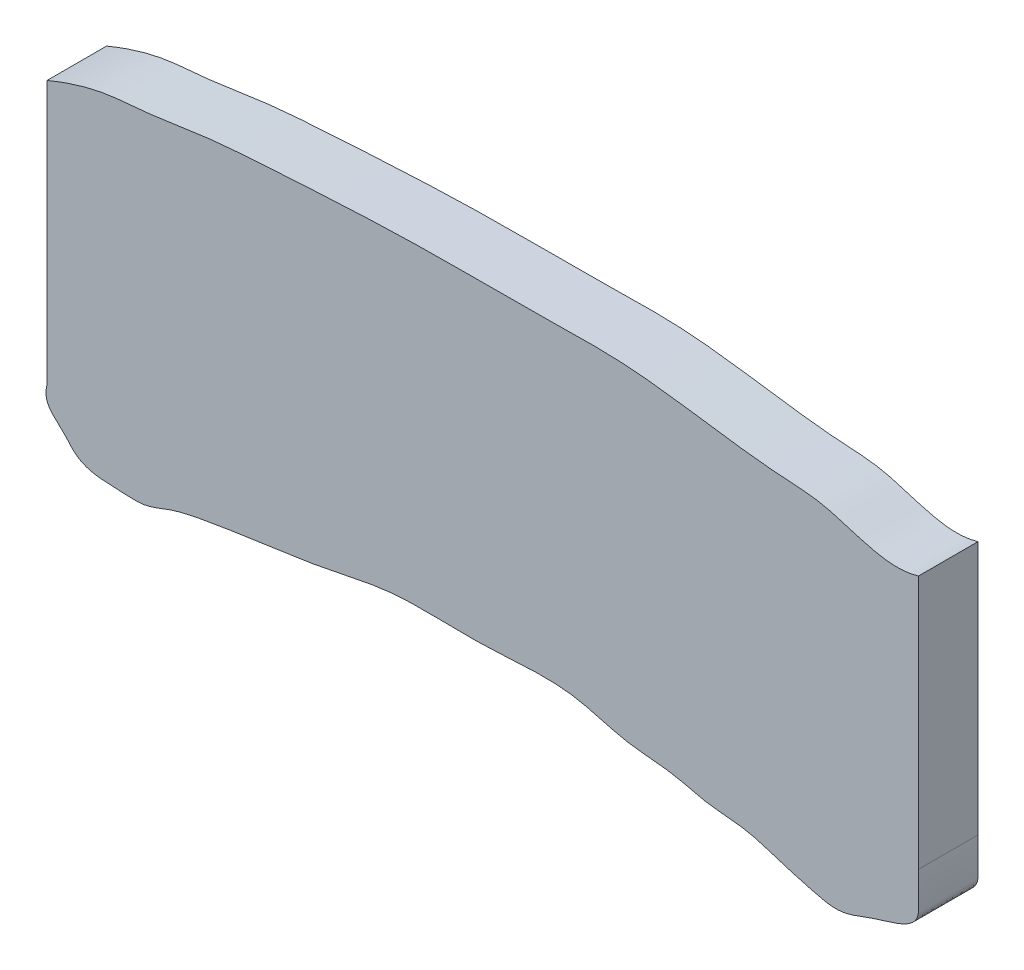
SolidWorks part; units mm, degrees
ref_plane "Front Plane" through (0, 0, 0) normal (0, 0, 1) x (1, 0, 0)
ref_plane "Top Plane" through (0, 0, 0) normal (0, 1, 0) x (1, 0, 0)
ref_plane "Right Plane" through (0, 0, 0) normal (1, 0, 0) x (0, 0, -1)
sketch "Sketch1" plane through (0, 0, 0) normal (0, 0, 1) x (1, 0, 0)
  line L0 (-13.2571, 28.2585) -> (-13.2571, 12.0434)
  line L1 (-68.8776, 11.0226) -> (-68.8776, 27.8463)
  spline S0 degree 3 poles (-68.8776, 11.0226) (-69.1801, 9.8889) (-68.0385, 9.3188) (-67.1607, 8.0756) (-65.9525, 7.5127) (-64.435, 7.5357) (-62.6555, 7.3277) (-61.2181, 8.0166) (-59.5799, 8.4425) (-57.5977, 8.7628) (-54.8435, 9.1995) (-51.1925, 9.6418) (-47.4681, 10.6219) (-43.8164, 10.5816) (-39.9184, 10.5067) (-35.7935, 11.0552) (-31.9769, 9.6444) (-29.1383, 9.6213) (-26.6693, 8.8531) (-24.2416, 8.849) (-22.112, 8.0441) (-20.2401, 7.5583) (-18.2151, 6.9843) (-16.0356, 8.0937) (-13.1856, 8.6046) (-13.2892, 10.5854) (-13.2333, 11.3544) (-13.2571, 12.0434) knots 0 0 0 0 0.040134 0.058143 0.073418 0.10314 0.132113 0.159261 0.179308 0.215301 0.257645 0.316225 0.395794 0.445168 0.494531 0.587891 0.644114 0.690569 0.72572 0.770043 0.808074 0.835934 0.866456 0.905518 0.960778 0.966812 1 1 1 1
  spline S1 degree 3 poles (-68.8776, 27.8463) (-67.7811, 28.2991) (-65.5796, 29.0694) (-62.2297, 29.2069) (-59.0077, 29.7964) (-55.4848, 30.0678) (-51.026, 30.3316) (-44.7117, 30.6413) (-38.3489, 30.5368) (-30.374, 30.768) (-24.7073, 29.4673) (-18.1835, 29.2539) (-15.4974, 27.6047) (-13.2571, 28.2585) knots 0 0 0 0 0.063691 0.123158 0.178342 0.238804 0.311997 0.417417 0.576851 0.652664 0.843233 0.885213 1 1 1 1
extrude "Extrude1" add sketch "Sketch1" along normal blind 3.8
